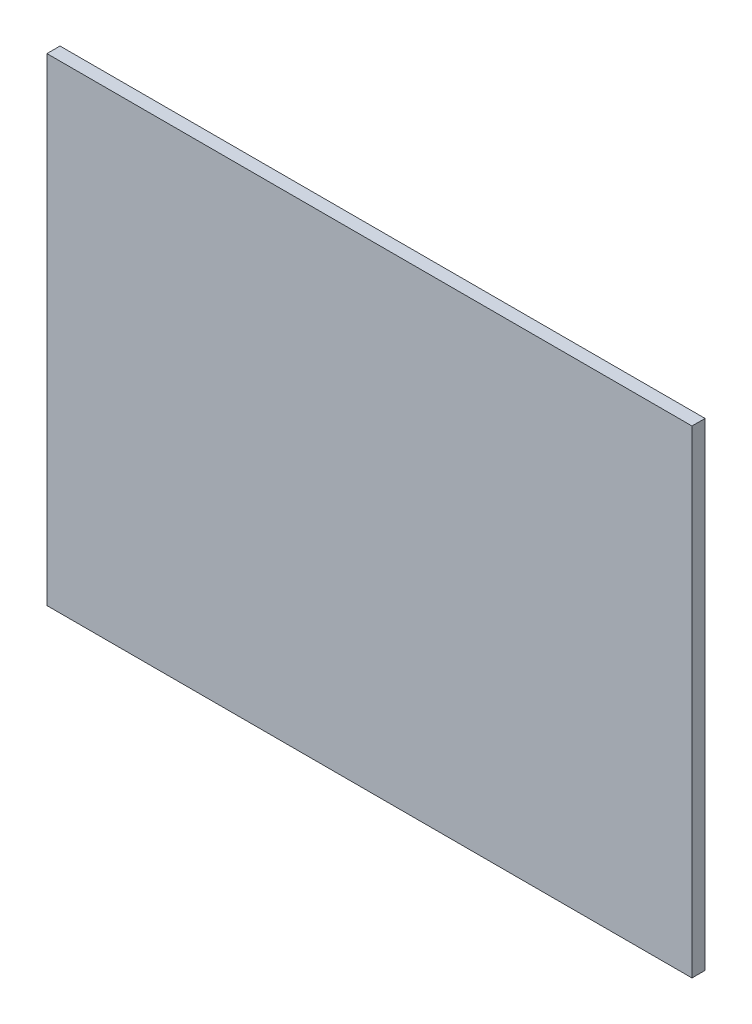
SolidWorks part; units mm, degrees
ref_plane "Front Plane" through (0, 0, 0) normal (0, 0, 1) x (1, 0, 0)
ref_plane "Top Plane" through (0, 0, 0) normal (0, 1, 0) x (1, 0, 0)
ref_plane "Right Plane" through (0, 0, 0) normal (1, 0, 0) x (0, 0, -1)
sketch "Sketch1" plane through (0, 0, 0) normal (0, 0, 1) x (1, 0, 0)
  line L1 (-49.25, 36.5) -> (49.25, 36.5)
  line L2 (-49.25, 36.5) -> (-49.25, -36.5)
  line L3 (-49.25, -36.5) -> (49.25, -36.5)
  line L4 (49.25, 36.5) -> (49.25, -36.5)
  line L5 (-49.25, 36.5) -> (49.25, -36.5) construction
  line L6 (-49.25, -36.5) -> (49.25, 36.5) construction
  point P0 (0, 0)
  dimension "D1" = 98.5
  dimension "D2" = 73
extrude "Boss-Extrude1" add sketch "Sketch1" along normal blind 2
